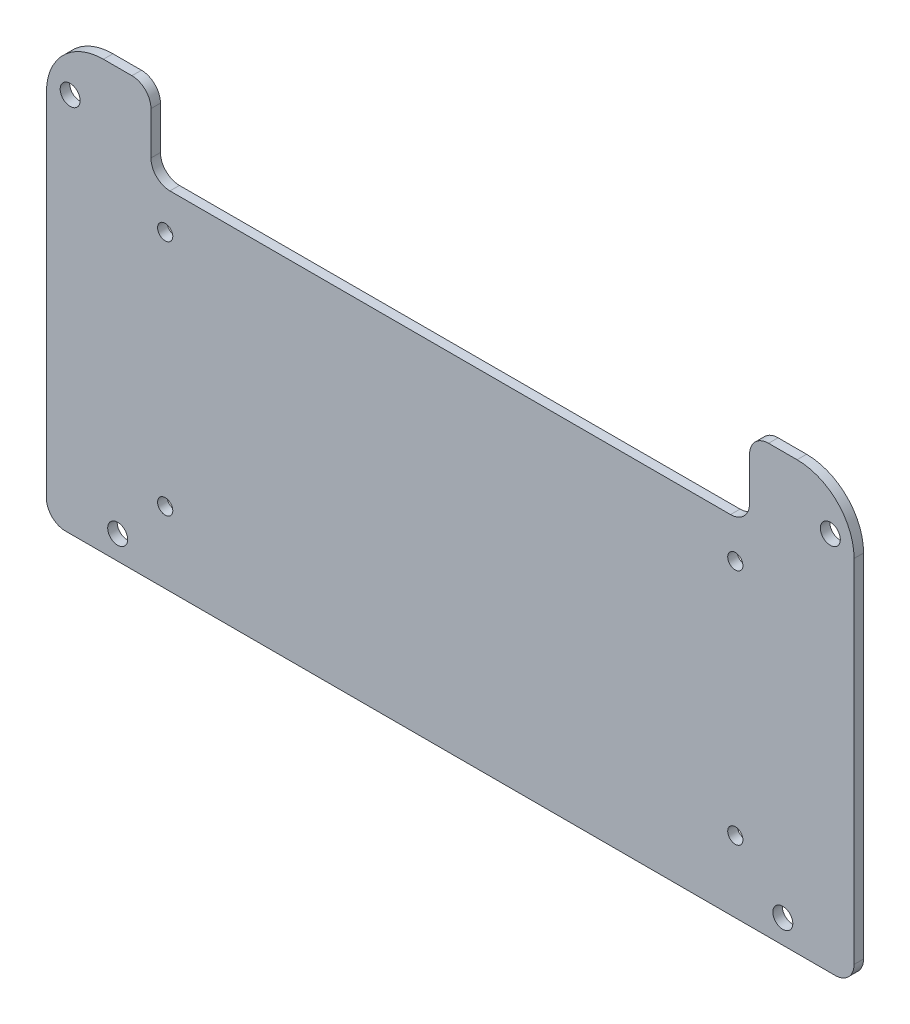
SolidWorks part; units mm, degrees
ref_plane "前视基准面" through (0, 0, 0) normal (0, 0, 1) x (1, 0, 0)
ref_plane "上视基准面" through (0, 0, 0) normal (0, 1, 0) x (1, 0, 0)
ref_plane "右视基准面" through (0, 0, 0) normal (1, 0, 0) x (0, 0, -1)
sketch "草图1" plane through (0, 0, 0) normal (0, 0, 1) x (1, 0, 0)
  line L1 (-95.625, 57.7896) -> (74.375, 57.7896)
  line L2 (-95.625, 57.7896) -> (-95.625, -32.2104)
  line L3 (-95.625, -32.2104) -> (74.375, -32.2104)
  line L4 (74.375, 57.7896) -> (74.375, -32.2104)
  dimension "D1" = 170
  dimension "D2" = 90
  dimension "D3" = 57.7896
extrude "凸台-拉伸1" add sketch "草图1" along normal blind 2
sketch "草图4" plane through (0, 0, 2) normal (0, 0, 1) x (1, 0, 0)
  line L0 (-95.625, -32.2104) -> (74.375, -32.2104) construction
  line L1 (74.375, -32.2104) -> (74.375, 57.7896) construction
  line L2 (-10.625, -42.2104) -> (-10.625, -50042.2104) construction
  line L3 (74.375, 57.7896) -> (-95.625, 57.7896) construction
  line L4 (-95.625, 57.7896) -> (-95.625, -32.2104) construction
  circle A0 centre (59.375, -27.2104) radius 2.1
  circle A1 centre (-80.625, -27.2104) radius 2.1
  circle A2 centre (69.375, 47.7896) radius 2.1
  circle A3 centre (-90.625, 47.7896) radius 2.1
  point P8 (-10.625, -32.2104)
  dimension "D1" = 4.2
  dimension "D4" = 4.2
  dimension "D9" = 4.2
  dimension "D2" = 5
  dimension "D3" = 15
  dimension "D5" = 10
  dimension "D6" = 5
  dimension "D7" = 5
  dimension "D8" = 10
extrude "切除-拉伸5" cut sketch "草图4" against normal blind 10
fillet "圆角1" radius 4 2 edges at (-95.625, -32.2104, 1) (74.375, -32.2104, 1)
sketch "草图5" plane through (0, 0, 2) normal (0, 0, 1) x (1, 0, 0)
  line L1 (-73.625, 40.7896) -> (52.375, 40.7896)
  line L5 (74.375, -28.2104) -> (74.375, 57.7896) construction
  line L10 (-73.625, 57.7896) -> (-73.625, 40.7896)
  line L19 (-95.625, 14.7896) -> (102.9119, 14.7896) construction
  line L20 (-95.625, 57.7896) -> (-95.625, -28.2104) construction
  line L21 (74.375, 57.7896) -> (-95.625, 57.7896) construction
  line L24 (-4.625, 57.7896) -> (-73.625, 57.7896)
  line L27 (52.375, 47.7896) -> (52.375, 57.7896)
  line L28 (52.375, 57.7896) -> (2.375, 57.7896)
  line L30 (-4.625, 57.7896) -> (2.375, 57.7896)
  line L31 (52.375, 40.7896) -> (52.375, 47.7896)
  dimension "D1" = 22
  dimension "D7" = 17
  dimension "D9" = 22
extrude "切除-拉伸6" cut sketch "草图5" against normal through all
sketch "草图7" plane through (0, 0, 2) normal (0, 0, 1) x (1, 0, 0)
  line L7 (-10.625, -32.2104) -> (-10.625, -45.3561) construction
  line L8 (-91.625, -32.2104) -> (70.375, -32.2104) construction
  circle A10 centre (49.375, 32.7896) radius 1.6
  circle A11 centre (49.375, -17.2104) radius 1.6
  circle A12 centre (-70.625, -17.2104) radius 1.6
  circle A13 centre (-70.625, 32.7896) radius 1.6
  circle A17 centre (69.375, 47.7896) radius 2.1 construction
  dimension "D1" = 20
  dimension "D3" = 3.2
  dimension "D4" = 3.2
  dimension "D6" = 50
extrude "切除-拉伸7" cut sketch "草图7" against normal through all
fillet "圆角2" radius 4 4 edges at (52.375, 57.7896, 1) (-73.625, 57.7896, 1) (52.375, 40.7896, 1) (-73.625, 40.7896, 1)
fillet "圆角3" radius 12 2 edges at (-95.625, 57.7896, 1) (74.375, 57.7896, 1)
